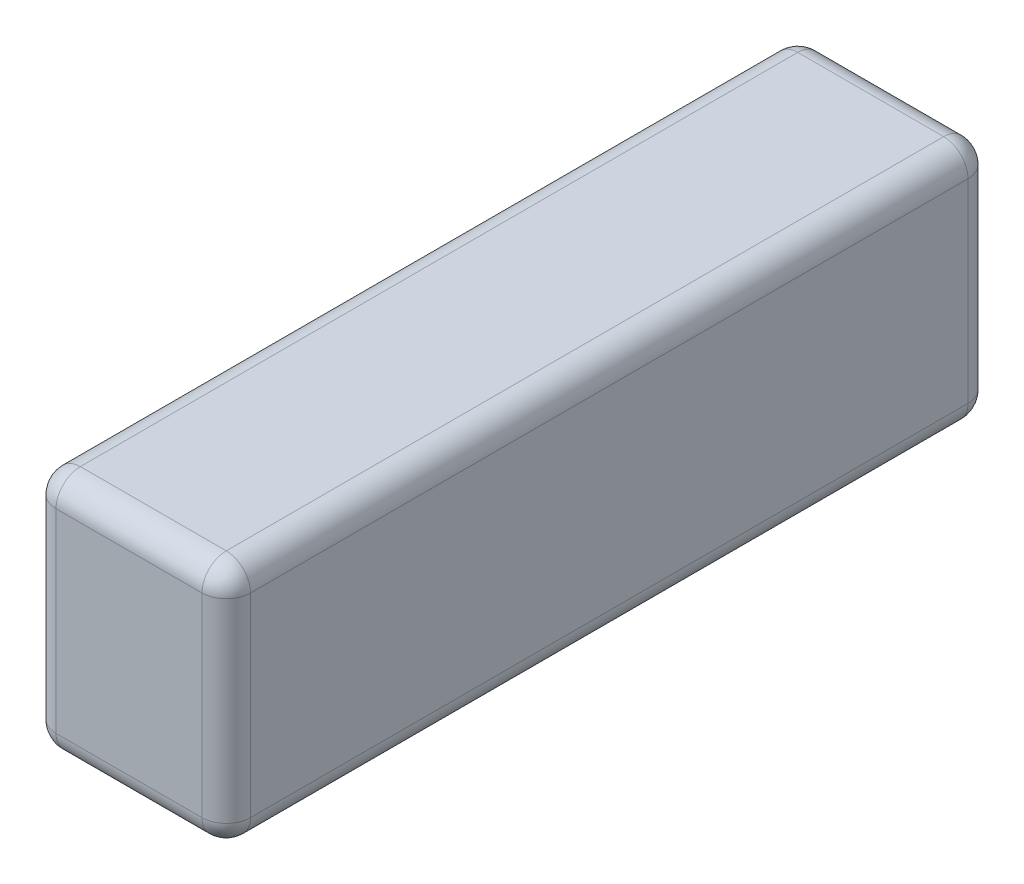
SolidWorks part; units mm, degrees
ref_plane "前视基准面" through (0, 0, 0) normal (0, 0, 1) x (1, 0, 0)
ref_plane "上视基准面" through (0, 0, 0) normal (0, 1, 0) x (1, 0, 0)
ref_plane "右视基准面" through (0, 0, 0) normal (1, 0, 0) x (0, 0, -1)
sketch "草图1" plane through (0, 0, 0) normal (0, 0, 1) x (1, 0, 0)
  line L1 (-8, 10) -> (8, 10)
  line L2 (-8, 10) -> (-8, -10)
  line L3 (-8, -10) -> (8, -10)
  line L4 (8, 10) -> (8, -10)
  line L5 (-8, 10) -> (8, -10) construction
  line L6 (-8, -10) -> (8, 10) construction
  point P0 (0, 0)
extrude "凸台-拉伸1" add sketch "草图1" along normal blind 63
ref_plane "基准面1" through (0, 0, 0) normal (0, 1, 0) x (1, 0, 0)
fillet "圆角1" radius 2 12 edges at (8, 0, 63) (8, 0, 0) (0, -10, 63) (8, -10, 31.5) (0, -10, 0) (-8, 0, 63) (-8, -10, 31.5) (-8, 0, 0) (8, 10, 31.5) (0, 10, 63) (-8, 10, 31.5) (0, 10, 0)
